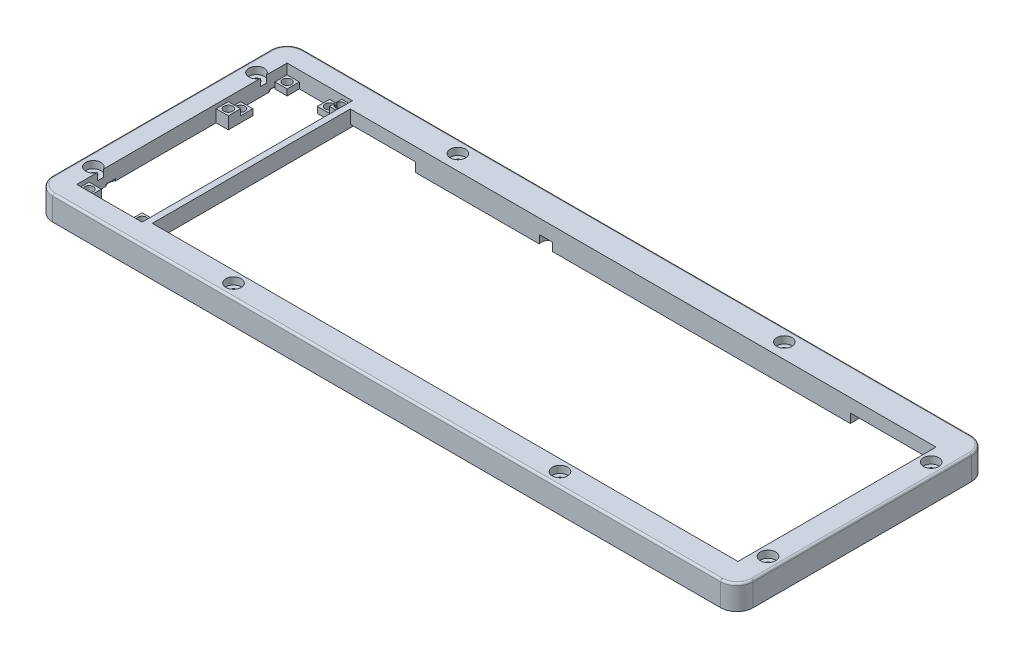
SolidWorks part; units mm, degrees
ref_plane "前视基准面" through (0, 0, 0) normal (0, 0, 1) x (1, 0, 0)
ref_plane "上视基准面" through (0, 0, 0) normal (0, 1, 0) x (1, 0, 0)
ref_plane "右视基准面" through (0, 0, 0) normal (1, 0, 0) x (0, 0, -1)
other "Configuration Table"
sketch "草图1" plane through (0, 0, 0) normal (0, 1, 0) x (1, 0, 0)
  line L1 (0, 0) -> (337.35, 0)
  line L2 (0, 0) -> (0, 116.87)
  line L3 (0, 116.87) -> (337.35, 116.87)
  line L4 (337.35, 0) -> (337.35, 116.87)
  line L5 (6.9, 109.97) -> (330.95, 109.97)
  line L6 (6.9, 109.97) -> (6.9, 6.9)
  line L7 (6.9, 6.9) -> (330.95, 6.9)
  line L8 (330.95, 109.97) -> (330.95, 6.9)
  dimension "D1" = 116.87
  dimension "D2" = 337.35
  dimension "D3" = 6.9
  dimension "D4" = 6.4
  dimension "D5" = 6.9
  dimension "D6" = 6.9
extrude "凸台-拉伸1" add sketch "草图1" along normal blind 8
fillet "圆角1" radius 5 4 edges at (0, 4, 0) (0, 4, -116.87) (337.35, 4, -116.87) (337.35, 4, 0)
sketch "草图2" plane through (0, 8, 0) normal (0, 1, 0) x (1, 0, 0)
  line L0 (167.17, 132.4281) -> (167.17, -13.3473) construction
  line L1 (0, 58.435) -> (337.35, 58.435) construction
  line L2 (0, 111.87) -> (0, 5) construction
  line L3 (337.35, 5) -> (337.35, 111.87) construction
  line L4 (23.7897, 113.42) -> (281.2218, 113.42) construction
  line L5 (3.45, 113.0437) -> (3.45, 3.45) construction
  line L6 (3.45, 3.45) -> (334.15, 3.45) construction
  line L7 (334.15, 3.45) -> (334.15, 110.0858) construction
  line L8 (332.35, 116.87) -> (5, 116.87) construction
  line L9 (330.95, 109.97) -> (6.9, 109.97) construction
  line L10 (6.9, 109.97) -> (6.9, 6.9) construction
  line L11 (6.9, 6.9) -> (330.95, 6.9) construction
  line L12 (5, 0) -> (332.35, 0) construction
  line L13 (330.95, 6.9) -> (330.95, 109.97) construction
  point P26 (87.17, 113.42)
  point P27 (247.17, 113.42)
  point P28 (247.17, 3.45)
  point P29 (87.17, 3.45)
  point P30 (3.45, 18.435)
  point P31 (334.15, 98.435)
  point P32 (3.45, 98.435)
  point P33 (334.15, 18.435)
  dimension "D1" = 167.17
  dimension "D2" = 160
  dimension "D3" = 80
hole_wizard "Ø3.2 (3.2) 直径孔1" positions "草图3" profile "草图4" hole size "Ø3.2" standard "ANSI Metric" end condition through all
sketch "草图3" plane through (0, 8, 0) normal (0, 1, 0) x (1, 0, 0)
  point P0 (3.45, 98.435)
  point P3 (87.17, 113.42)
  point P6 (247.17, 113.42)
  point P9 (334.15, 98.435)
  point P12 (334.15, 18.435)
  point P15 (247.17, 3.45)
  point P18 (87.17, 3.45)
  point P21 (3.45, 18.435)
sketch "草图4" plane through (3.45, 8, -98.435) normal (1, 0, 0) x (0, 0, 1)
  line L0 (0, 0) -> (0, 8)
  line L1 (0, 8) -> (1.6, 8)
  line L2 (1.6, 8) -> (1.6, 0)
  line L5 (1.6, 0) -> (0, 0)
  line L11 (0, -6.35) -> (0, 107.95) construction
  dimension "通孔孔直径" = 3.2
  dimension "通孔孔深度" = 8
sketch "草图5" plane through (0, 0, -109.97) normal (0, 0, 1) x (1, 0, 0)
  line L0 (330.95, 0) -> (6.9, 0) construction
  line L1 (41.9, 0) -> (73.9, 0)
  line L2 (41.9, 0) -> (41.9, 1.5)
  line L3 (41.9, 1.5) -> (73.9, 1.5)
  line L4 (73.9, 0) -> (73.9, 1.5)
  line L5 (6.9, 8) -> (6.9, 0) construction
  dimension "D1" = 35
  dimension "D2" = 32
  dimension "D3" = 1.5
extrude "切除-拉伸1" cut sketch "草图5" against normal through all
sketch "草图6" plane through (0, 0, -109.97) normal (0, 0, 1) x (1, 0, 0)
  line L0 (330.95, 8) -> (6.9, 8) construction
  line L1 (41.9, 0) -> (38.9, 0)
  line L2 (41.9, 0) -> (41.9, 8)
  line L3 (41.9, 8) -> (38.9, 8)
  line L4 (38.9, 0) -> (38.9, 8)
  dimension "D1" = 3
extrude "凸台-拉伸2" add sketch "草图6" along normal up to next
sketch "草图7" plane through (0, 0, -109.97) normal (0, 0, 1) x (1, 0, 0)
  line L1 (73.9, 0) -> (330.95, 0)
  line L2 (73.9, 0) -> (73.9, 8)
  line L3 (73.9, 8) -> (330.95, 8)
  line L4 (330.95, 0) -> (330.95, 8)
extrude "凸台-拉伸3" add sketch "草图7" along normal blind 4
sketch "草图8" plane through (0, 0, 0) normal (0, -1, 0) x (1, 0, 0)
  line L1 (330.95, -105.97) -> (73.9, -105.97)
  line L2 (330.95, -105.97) -> (330.95, -109.97)
  line L3 (330.95, -109.97) -> (73.9, -109.97)
  line L4 (73.9, -105.97) -> (73.9, -109.97)
extrude "凸台-拉伸4" add sketch "草图8" along normal blind 3
sketch "草图9" plane through (0, 8, 0) normal (0, 1, 0) x (1, 0, 0)
  circle A0 centre (137.8085, 107.33) radius 3.5
  circle A1 centre (328.3085, 74.31) radius 3.5
  circle A2 centre (328.3085, 13.35) radius 3.5
  circle A3 centre (262.2685, 9.54) radius 3.5
  circle A4 centre (92.0885, 9.54) radius 3.5
  circle A5 centre (22.2385, 9.54) radius 3.5
  circle A6 centre (9.5385, 23.51) radius 3.5
  circle A7 centre (9.5385, 103.52) radius 3.5
  dimension "D1" = 7
sketch "草图11" plane through (330.95, 0, 0) normal (-1, 0, 0) x (0, 0, 1)
  line L1 (-6.9, 8) -> (-105.97, 8)
  line L2 (-6.9, 8) -> (-6.9, -3)
  line L3 (-6.9, -3) -> (-105.97, -3)
  line L4 (-105.97, 8) -> (-105.97, -3)
extrude "凸台-拉伸5" add sketch "草图11" along normal blind 2
sketch "草图13" plane through (0, 0, -105.97) normal (0, 0, 1) x (1, 0, 0)
  line L0 (328.95, 8) -> (73.9, 8) construction
  line L1 (328.95, -3) -> (286.95, -3)
  line L2 (328.95, -3) -> (328.95, 1.5)
  line L3 (328.95, 1.5) -> (286.95, 1.5)
  line L4 (286.95, -3) -> (286.95, 1.5)
  dimension "D1" = 6.5
  dimension "D2" = 42
extrude "切除-拉伸2" cut sketch "草图13" against normal through all
sketch "草图14" plane through (0, 0, -6.9) normal (0, 0, -1) x (-1, 0, 0)
  line L0 (-41.9, 0) -> (-328.95, 0) construction
  line L1 (-233.95, 0) -> (-112.45, 0)
  line L2 (-233.95, 0) -> (-233.95, 1.5)
  line L3 (-233.95, 1.5) -> (-112.45, 1.5)
  line L4 (-112.45, 0) -> (-112.45, 1.5)
  line L6 (-41.9, 8) -> (-328.95, 8) construction
  line L7 (-328.95, 0) -> (-328.95, 8) construction
  dimension "D1" = 6.5
  dimension "D2" = 95
  dimension "D3" = 216.5
extrude "切除-拉伸3" cut sketch "草图14" against normal through all
sketch "草图16" plane through (0, 0, -109.97) normal (0, 0, 1) x (1, 0, 0)
  line L1 (41.9, 8) -> (73.9, 8)
  line L2 (41.9, 8) -> (41.9, 1.5)
  line L3 (41.9, 1.5) -> (73.9, 1.5)
  line L4 (73.9, 8) -> (73.9, 1.5)
extrude "凸台-拉伸7" add sketch "草图16" along normal up to surface (4 mm away) up to face at (229.9333, 2.1667, -105.97)
sketch "草图17" plane through (330.95, 0, 0) normal (1, 0, 0) x (0, 0, -1)
  line L8 (109.97, -3) -> (109.97, 0)
  line L9 (109.97, 0) -> (6.9, 0)
  line L10 (6.9, 0) -> (6.9, -3)
  line L11 (6.9, -3) -> (109.97, -3)
  line L12 (109.97, -3) -> (109.97, 0)
  line L13 (109.97, 0) -> (6.9, 0)
  line L14 (6.9, 0) -> (6.9, -3)
  line L15 (6.9, -3) -> (109.97, -3)
  dimension "D1" = 0
extrude "切除-拉伸4" cut sketch "草图17" against normal blind 0.1
sketch "草图18" plane through (0, 0, -6.9) normal (0, 0, -1) x (-1, 0, 0)
  line L16 (-233.95, 0) -> (-233.95, 1.5)
  line L17 (-233.95, 1.5) -> (-112.45, 1.5)
  line L18 (-112.45, 1.5) -> (-112.45, 0)
  line L19 (-112.45, 0) -> (-41.9, 0)
  line L20 (-41.9, 0) -> (-41.9, 8)
  line L21 (-41.9, 8) -> (-328.95, 8)
  line L22 (-328.95, 8) -> (-328.95, 0)
  line L23 (-328.95, 0) -> (-233.95, 0)
  line L24 (-233.95, 0) -> (-233.95, 1.5)
  line L25 (-233.95, 1.5) -> (-112.45, 1.5)
  line L26 (-112.45, 1.5) -> (-112.45, 0)
  line L27 (-112.45, 0) -> (-41.9, 0)
  line L28 (-41.9, 0) -> (-41.9, 8)
  line L29 (-41.9, 8) -> (-328.95, 8)
  line L30 (-328.95, 8) -> (-328.95, 0)
  line L31 (-328.95, 0) -> (-233.95, 0)
  dimension "D1" = 0
extrude "凸台-拉伸8" add sketch "草图18" along normal blind 2
sketch "草图19" plane through (0, 0, 0) normal (0, -1, 0) x (1, 0, 0)
  line L0 (112.45, 0) -> (112.45, -8.9) construction
  line L1 (41.9, -8.9) -> (112.45, -8.9)
  line L2 (41.9, -8.9) -> (41.9, -6.9)
  line L3 (41.9, -6.9) -> (112.45, -6.9)
  line L4 (112.45, -8.9) -> (112.45, -6.9)
  line L6 (233.95, -8.9) -> (328.95, -8.9)
  line L7 (233.95, -8.9) -> (233.95, -6.9)
  line L8 (233.95, -6.9) -> (328.95, -6.9)
  line L9 (328.95, -8.9) -> (328.95, -6.9)
  dimension "D1" = 2
extrude "凸台-拉伸9" add sketch "草图19" along normal up to surface (3 mm away) up to face at (329.9, -3, -58.435)
sketch "草图10" plane through (0, -3, 0) normal (0, -1, 0) x (1, 0, 0)
  circle A2 centre (137.8085, -107.33) radius 3.5
  circle A3 centre (137.8085, -107.33) radius 3.5
  dimension "D1" = 0
sketch "草图20" plane through (0, -3, 0) normal (0, -1, 0) x (1, 0, 0)
  circle A58 centre (92.0885, -9.54) radius 3.5
  circle A59 centre (92.0885, -9.54) radius 3.5
  circle A120 centre (262.2685, -9.54) radius 3.5
  circle A121 centre (262.2685, -9.54) radius 3.5
  circle A123 centre (328.3085, -13.35) radius 3.5
  circle A124 centre (328.3085, -13.35) radius 3.5
  circle A126 centre (328.3085, -74.31) radius 3.5
  circle A127 centre (328.3085, -74.31) radius 3.5
  circle A129 centre (137.8085, -107.33) radius 3.5
  circle A130 centre (137.8085, -107.33) radius 3.5
  circle A132 centre (22.2385, -9.54) radius 3.5
  circle A133 centre (22.2385, -9.54) radius 3.5
  circle A135 centre (9.5385, -23.51) radius 3.5
  circle A136 centre (9.5385, -23.51) radius 3.5
  circle A138 centre (9.5385, -103.52) radius 3.5
  circle A139 centre (9.5385, -103.52) radius 3.5
  dimension "D1" = 0
  dimension "D2" = 0
  dimension "D3" = 0
  dimension "D4" = 0
  dimension "D5" = 0
  dimension "D6" = 0
  dimension "D7" = 0
  dimension "D8" = 0
extrude "切除-拉伸5" cut sketch "草图20" against normal blind 4
sketch "草图21" plane through (0, 8, 0) normal (0, 1, 0) x (1, 0, 0)
  line L4 (-3, 111.87) -> (-3, 5)
  line L5 (5, -3) -> (332.35, -3)
  line L6 (340.35, 5) -> (340.35, 111.87)
  line L7 (332.35, 119.87) -> (5, 119.87)
  line L8 (0, 111.87) -> (0, 5)
  line L9 (5, 0) -> (332.35, 0)
  line L10 (337.35, 5) -> (337.35, 111.87)
  line L11 (332.35, 116.87) -> (5, 116.87)
  line L12 (0, 111.87) -> (0, 5)
  line L13 (5, 0) -> (332.35, 0)
  line L14 (337.35, 5) -> (337.35, 111.87)
  line L15 (332.35, 116.87) -> (5, 116.87)
  arc A4 (-3, 5) -> (5, -3) centre (5, 5) ccw
  arc A5 (332.35, -3) -> (340.35, 5) centre (332.35, 5) ccw
  arc A6 (340.35, 111.87) -> (332.35, 119.87) centre (332.35, 111.87) ccw
  arc A7 (5, 119.87) -> (-3, 111.87) centre (5, 111.87) ccw
  arc A8 (0, 5) -> (5, 0) centre (5, 5) ccw
  arc A9 (332.35, 0) -> (337.35, 5) centre (332.35, 5) ccw
  arc A10 (337.35, 111.87) -> (332.35, 116.87) centre (332.35, 111.87) ccw
  arc A11 (5, 116.87) -> (0, 111.87) centre (5, 111.87) ccw
  arc A12 (0, 5) -> (5, 0) centre (5, 5) ccw
  arc A13 (332.35, 0) -> (337.35, 5) centre (332.35, 5) ccw
  arc A14 (337.35, 111.87) -> (332.35, 116.87) centre (332.35, 111.87) ccw
  arc A15 (5, 116.87) -> (0, 111.87) centre (5, 111.87) ccw
  dimension "D1" = 0
  dimension "D2" = 3
extrude "凸台-拉伸10" add sketch "草图21" against normal blind 12
sketch "草图22" plane through (0, 0, -119.87) normal (0, 0, -1) x (-1, 0, 0)
  line L0 (-332.35, -4) -> (-5, -4) construction
  line L1 (-55.9085, -4) -> (-11.002, -4)
  line L2 (-55.9085, -4) -> (-55.9085, 0)
  line L3 (-55.9085, 0) -> (-11.002, 0)
  line L4 (-11.002, -4) -> (-11.002, 0)
  line L5 (-55.9085, -19.7723) -> (-55.9085, 0) construction
  line L6 (-11.002, -23.2723) -> (-11.002, 0) construction
extrude "切除-拉伸6" cut sketch "草图22" against normal up to surface (9.9 mm away) up to face at (22.9, 4, -109.97)
sketch "草图23" plane through (0, 0, 0) normal (0, -1, 0) x (1, 0, 0)
  line L0 (6.9, -101.2203) -> (6.9, -25.8097) construction
  line L1 (6.9, -6.9) -> (12.9, -6.9)
  line L2 (6.9, -6.9) -> (6.9, -12.9)
  line L3 (6.9, -12.9) -> (12.9, -12.9)
  line L4 (12.9, -6.9) -> (12.9, -12.9)
  line L5 (38.9, -6.9) -> (32.9, -6.9)
  line L6 (38.9, -6.9) -> (38.9, -12.9)
  line L7 (38.9, -12.9) -> (32.9, -12.9)
  line L8 (32.9, -6.9) -> (32.9, -12.9)
  line L9 (6.9, -109.97) -> (12.9, -109.97)
  line L10 (6.9, -109.97) -> (6.9, -103.97)
  line L11 (6.9, -103.97) -> (12.9, -103.97)
  line L12 (12.9, -109.97) -> (12.9, -103.97)
  line L17 (6.9, -81.17) -> (12.9, -81.17)
  line L18 (6.9, -81.17) -> (6.9, -87.17)
  line L19 (6.9, -87.17) -> (12.9, -87.17)
  line L20 (12.9, -81.17) -> (12.9, -87.17)
  line L22 (33.7, -103.97) -> (27.7, -103.97)
  line L23 (33.7, -103.97) -> (33.7, -109.97)
  line L24 (33.7, -109.97) -> (27.7, -109.97)
  line L25 (27.7, -103.97) -> (27.7, -109.97)
  line L27 (38.9, -109.97) -> (6.9, -109.97) construction
  circle A0 centre (9.9, -106.97) radius 2.15
  circle A1 centre (30.7, -106.97) radius 2.15
  circle A2 centre (9.9, -84.17) radius 2.15
  dimension "D6" = 4.3
  dimension "D1" = 6
  dimension "D2" = 28.8
  dimension "D3" = 26.8
  dimension "D4" = 3
  dimension "D5" = 3
  dimension "D7" = 3
  dimension "D8" = 3
  dimension "D9" = 3
  dimension "D10" = 3
extrude "凸台-拉伸11" add sketch "草图23" against normal blind 3
sketch "草图26" plane through (0, 0, 0) normal (0, -1, 0) x (1, 0, 0)
  line L1 (33.7, -103.97) -> (38.9, -103.97)
  line L2 (33.7, -103.97) -> (33.7, -109.97)
  line L3 (33.7, -109.97) -> (38.9, -109.97)
  line L4 (38.9, -103.97) -> (38.9, -109.97)
  line L5 (6.9, -81.17) -> (12.9, -81.17)
  line L6 (6.9, -81.17) -> (6.9, -75.17)
  line L7 (6.9, -75.17) -> (12.9, -75.17)
  line L8 (12.9, -81.17) -> (12.9, -75.17)
  dimension "D1" = 6
  dimension "D2" = 6
extrude "凸台-拉伸12" add sketch "草图26" against normal blind 6
sketch "草图27" plane through (0, 3, 0) normal (0, 1, 0) x (1, 0, 0)
  line L12 (6.9, 12.9) -> (6.9, 6.9)
  line L13 (6.9, 6.9) -> (12.9, 6.9)
  line L14 (12.9, 6.9) -> (12.9, 12.9)
  line L15 (12.9, 12.9) -> (6.9, 12.9)
  line L16 (6.9, 12.9) -> (6.9, 6.9)
  line L17 (6.9, 6.9) -> (12.9, 6.9)
  line L18 (12.9, 6.9) -> (12.9, 12.9)
  line L19 (12.9, 12.9) -> (6.9, 12.9)
  line L24 (38.9, 6.9) -> (38.9, 12.9)
  line L25 (38.9, 12.9) -> (32.9, 12.9)
  line L26 (32.9, 12.9) -> (32.9, 6.9)
  line L27 (32.9, 6.9) -> (38.9, 6.9)
  line L28 (38.9, 6.9) -> (38.9, 12.9)
  line L29 (38.9, 12.9) -> (32.9, 12.9)
  line L30 (32.9, 12.9) -> (32.9, 6.9)
  line L31 (32.9, 6.9) -> (38.9, 6.9)
  dimension "D1" = 0
  dimension "D2" = 0
extrude "凸台-拉伸13" add sketch "草图27" along normal up to surface (3 mm away) up to face at (36.3, 6, -106.97)
sketch "草图28" plane through (0, 6, 0) normal (0, 1, 0) x (1, 0, 0)
  line L0 (6.9, 109.97) -> (6.9, 6.9) construction
  line L1 (12.9, 81.17) -> (6.9, 81.17) construction
  line L2 (6.9, 6.9) -> (38.9, 6.9) construction
  line L3 (32.9, 6.9) -> (32.9, 12.9) construction
  line L4 (33.7, 109.97) -> (38.9, 109.97) construction
  circle A0 centre (35.9, 106.97) radius 2.15
  circle A1 centre (35.9, 9.9) radius 2.15
  circle A2 centre (9.9, 9.9) radius 2.15
  circle A3 centre (9.9, 78.17) radius 2.15
  dimension "D1" = 4.3
  dimension "D2" = 3
  dimension "D3" = 3
  dimension "D4" = 3
  dimension "D5" = 3
  dimension "D6" = 3
extrude "切除-拉伸7" cut sketch "草图28" against normal blind 4.2
sketch "草图29" plane through (0, 6, 0) normal (0, 1, 0) x (1, 0, 0)
  line L0 (33.7, 103.97) -> (33.7, 109.97) construction
  line L1 (33.7, 107.431) -> (33.8, 107.431)
  line L2 (33.7, 107.431) -> (33.7, 106.509)
  line L3 (33.7, 106.509) -> (33.8, 106.509)
  line L4 (33.8, 107.431) -> (33.8, 106.509)
  line L5 (33.7, 106.97) -> (36.6329, 106.97) construction
  circle A1 centre (35.9, 106.97) radius 2.15 construction
  dimension "D1" = 0.1
extrude "切除-拉伸8" cut sketch "草图29" against normal up to surface (4.2 mm away) up to face at (35.9, 1.8, -104.82)
sketch "草图30" plane through (0, 8, 0) normal (0, 1, 0) x (1, 0, 0)
  circle A0 centre (87.17, 113.42) radius 3.75
  circle A1 centre (247.17, 113.42) radius 3.75
  circle A2 centre (334.15, 98.435) radius 3.75
  circle A3 centre (334.15, 18.435) radius 3.75
  circle A4 centre (87.17, 3.45) radius 3.75
  circle A5 centre (247.17, 3.45) radius 3.75
  circle A6 centre (3.45, 18.435) radius 3.75
  circle A7 centre (3.45, 98.435) radius 3.75
  dimension "D1" = 7.5
extrude "切除-拉伸9" cut sketch "草图30" against normal offset from surface (3.5 mm away) 4.5 up to face at (166.2195, 0, -112.4133)
fillet "圆角3" radius 1 8 edges at (-0.6569, 8, 0.6569) (-3, 8, -58.435) (-0.6569, 8, -117.5269) (168.675, 8, -119.87) (338.0069, 8, -117.5269) (340.35, 8, -58.435) (338.0069, 8, 0.6569) (168.675, 8, 3)
sketch "草图31" plane through (0, 6, 0) normal (0, 1, 0) x (1, 0, 0)
  line L0 (9.9, 9.9) -> (35.9, 9.9) construction
  line L1 (35.9, 9.9) -> (35.9, 106.97) construction
  line L2 (9.9, 84.17) -> (9.9, 9.9) construction
  line L4 (38.9, 109.97) -> (38.9, 6.9) construction
  line L5 (38.9, 6.9) -> (6.9, 6.9) construction
  line L6 (22.9, 6.9) -> (22.9, 109.97) construction
  line L7 (38.9, 109.97) -> (6.9, 109.97) construction
  line L8 (38.9, 58.435) -> (6.9, 58.435) construction
  line L9 (0, 58.435) -> (337.35, 58.435) construction
  circle A0 centre (9.9, 78.17) radius 2.15 construction
  arc A1 (33.8, 106.509) -> (33.8, 107.431) centre (35.9, 106.97) ccw construction
  dimension "D5" = 68.27
  dimension "D6" = 97.07
  dimension "D1" = 103.07
  dimension "D2" = 32
  dimension "D3" = 26
  dimension "D4" = 3
